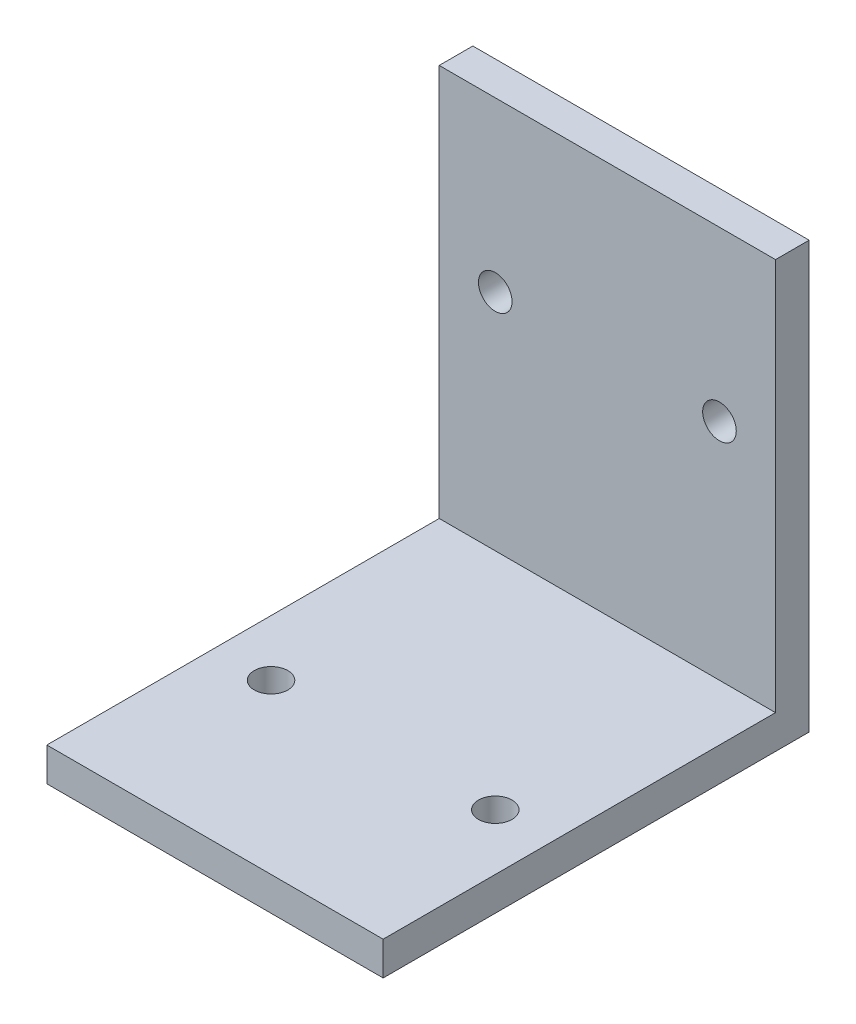
SolidWorks part; units mm, degrees
ref_plane "前视基准面" through (0, 0, 0) normal (0, 0, 1) x (1, 0, 0)
ref_plane "上视基准面" through (0, 0, 0) normal (0, 1, 0) x (1, 0, 0)
ref_plane "右视基准面" through (0, 0, 0) normal (1, 0, 0) x (0, 0, -1)
sketch "草图1" plane through (0, 0, 0) normal (0, 0, 1) x (1, 0, 0)
  line L1 (-15, 19) -> (15, 19)
  line L2 (-15, 19) -> (-15, -19)
  line L3 (-15, -19) -> (15, -19)
  line L4 (15, 19) -> (15, -19)
  line L5 (-15, 19) -> (15, -19) construction
  line L6 (-15, -19) -> (15, 19) construction
  point P0 (0, 0)
  dimension "D1" = 30
  dimension "D2" = 38
extrude "凸台-拉伸1" add sketch "草图1" along normal blind 3
sketch "草图2" plane through (0, 0, 3) normal (0, 0, 1) x (1, 0, 0)
  line L0 (15, -19) -> (15, 19) construction
  line L1 (-15, -19) -> (15, -19)
  line L2 (-15, -19) -> (-15, -16)
  line L3 (-15, -16) -> (15, -16)
  line L4 (15, -19) -> (15, -16)
  dimension "D1" = 3
extrude "凸台-拉伸2" add sketch "草图2" along normal blind 35
sketch "草图3" plane through (0, 0, 3) normal (0, 0, 1) x (1, 0, 0)
  line L0 (15, -16) -> (15, 19) construction
  line L1 (-15, 19) -> (-15, -16) construction
  line L2 (15, 19) -> (-15, 19) construction
  circle A0 centre (-10, 4) radius 1.5
  circle A1 centre (10, 4) radius 1.5
  dimension "D1" = 3
  dimension "D2" = 3
  dimension "D3" = 5
  dimension "D4" = 5
  dimension "D5" = 15
  dimension "D6" = 15
extrude "切除-拉伸1" cut sketch "草图3" against normal blind 35
sketch "草图4" plane through (0, -16, 0) normal (0, 1, 0) x (1, 0, 0)
  line L1 (15, -38) -> (15, -3) construction
  line L2 (-15, -38) -> (-15, -3) construction
  line L3 (15, -38) -> (-15, -38) construction
  circle A0 centre (-10, -23) radius 1.5
  circle A1 centre (10, -23) radius 1.5
  point P11 (0, 0)
  dimension "D1" = 3
  dimension "D2" = 3
  dimension "D3" = 5
  dimension "D4" = 5
  dimension "D5" = 15
extrude "切除-拉伸2" cut sketch "草图4" against normal blind 35
